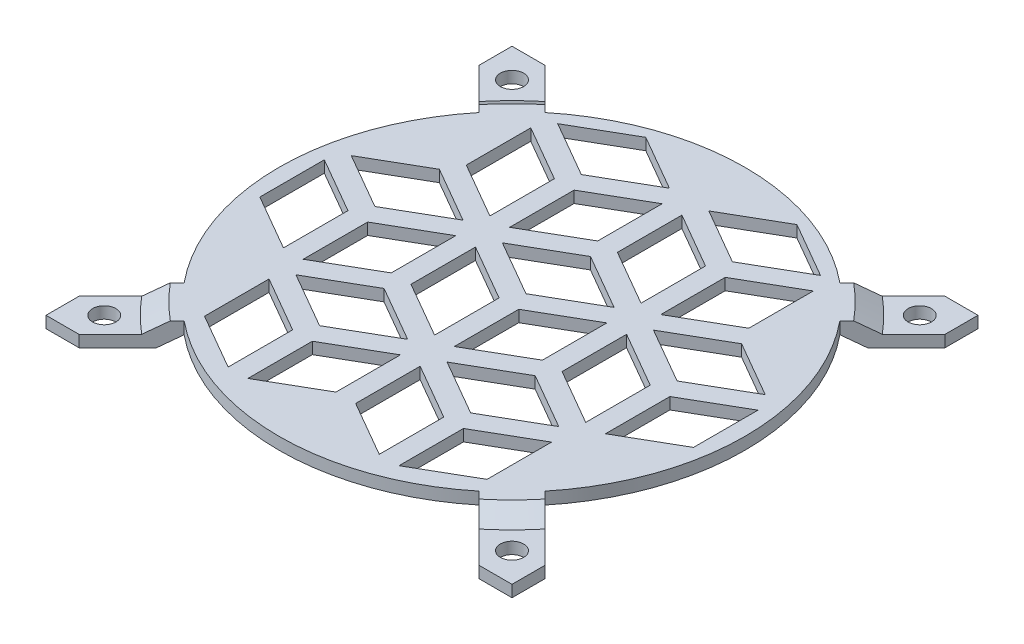
SolidWorks part; units mm, degrees
material "1.6523 (20NiCrMoS2-2)"
ref_plane "Спереди" through (0, 0, 0) normal (0, 0, 1) x (1, 0, 0)
ref_plane "Сверху" through (0, 0, 0) normal (0, 1, 0) x (1, 0, 0)
ref_plane "Справа" through (0, 0, 0) normal (1, 0, 0) x (0, 0, -1)
sketch "Эскиз1" plane through (0, 0, 0) normal (0, 1, 0) x (1, 0, 0)
  line L0 (-51.5147, -60) -> (-37.9711, -46.4564)
  line L1 (-60, 60) -> (-51.5147, 60)
  line L2 (-60, 60) -> (-60, 51.5147)
  line L3 (-60, -60) -> (-51.5147, -60)
  line L4 (60, 60) -> (60, 51.5147)
  line L5 (-60, 60) -> (60, -60) construction
  line L7 (-52.5, 52.5) -> (52.5, 52.5) construction
  line L8 (-52.5, 52.5) -> (-52.5, -52.5) construction
  line L9 (-52.5, -52.5) -> (52.5, -52.5) construction
  line L10 (52.5, 52.5) -> (52.5, -52.5) construction
  line L11 (-52.5, 52.5) -> (52.5, -52.5) construction
  line L13 (-60, -51.5147) -> (-46.4564, -37.9711)
  line L14 (-60, 51.5147) -> (-46.4564, 37.9711)
  line L15 (-51.5147, 60) -> (-37.9711, 46.4564)
  line L18 (51.5147, 60) -> (60, 60)
  line L20 (-60, -51.5147) -> (-60, -60)
  line L22 (-64.2426, 55.7574) -> (55.7574, -64.2426) construction
  line L23 (2.7392, 6.9819) -> (6.4592, 10.7018)
  line L25 (46.4564, -37.9711) -> (60, -51.5147)
  line L26 (-6.4592, 10.7018) -> (-2.7392, 6.9819)
  line L58 (-55.7574, 64.2426) -> (64.2426, -55.7574) construction
  line L59 (37.9711, -46.4564) -> (51.5147, -60)
  line L61 (46.4564, 37.9711) -> (60, 51.5147)
  line L65 (37.9711, 46.4564) -> (51.5147, 60)
  line L66 (60, -51.5147) -> (60, -60)
  line L67 (51.5147, -60) -> (60, -60)
  circle A10 centre (-52.5, -52.5) radius 3
  circle A11 centre (-52.5, 52.5) radius 3
  circle A12 centre (52.5, 52.5) radius 3
  circle A13 centre (52.5, -52.5) radius 3
  arc A14 (2.7392, 6.9819) -> (-2.7392, 6.9819) centre (0, 0) ccw
  arc A15 (6.4592, 10.7018) -> (-6.4592, 10.7018) centre (0, 0) ccw
  arc A44 (-37.9711, -46.4564) -> (37.9711, -46.4564) centre (0, 0) ccw
  arc A45 (46.4564, -37.9711) -> (46.4564, 37.9711) centre (0, 0) ccw
  arc A46 (37.9711, 46.4564) -> (-37.9711, 46.4564) centre (0, 0) ccw
  arc A47 (-46.4564, 37.9711) -> (-46.4564, -37.9711) centre (0, 0) ccw
  point P0 (0, 0)
  point P25 (-62.1213, 57.8787)
  point P26 (57.8787, -62.1213)
  point P27 (-57.8787, 62.1213)
  point P28 (62.1213, -57.8787)
  point P29 (-57.8787, -62.1213)
  point P30 (62.1213, 57.8787)
  point P31 (-62.1213, -57.8787)
  point P32 (57.8787, 62.1213)
  point P104 (-55.7574, -64.2426)
  point P105 (64.2426, 55.7574)
  point P106 (-64.2426, -55.7574)
  point P107 (55.7574, 64.2426)
  dimension "D15" = 6
  dimension "D16" = 6
  dimension "D17" = 6
  dimension "D18" = 6
  dimension "D1" = 120
  dimension "D2" = 120
  dimension "D13" = 105
  dimension "D14" = 105
  dimension "D21" = 6
  dimension "D22" = 6
extrude "Бобышка-Вытянуть1" add sketch "Эскиз1" along normal blind 6
sketch "Эскиз2" plane through (0, 0, 0) normal (0, -1, 0) x (1, 0, 0)
  circle A0 centre (0, 0) radius 65
  dimension "D1" = 130
extrude "Вырез-Вытянуть1" cut sketch "Эскиз2" against normal blind 3 draft 60
sketch "Эскиз3" plane through (0, 6, 0) normal (0, 1, 0) x (1, 0, 0)
  circle A0 centre (0, 0) radius 62.5
  dimension "D1" = 125
extrude "Вырез-Вытянуть2" cut sketch "Эскиз3" against normal blind 3 draft 60 flip side to cut
sketch "Sketch1" plane through (0, 6, 0) normal (0, 1, 0) x (1, 0, 0)
  line B0 (19.4556, 53.9141) -> (5.0736, 45.6106)
  line B1 (2.5356, 41.2147) -> (2.5356, 24.6078)
  line B2 (2.5356, 24.6078) -> (16.9176, 16.3043)
  line B3 (21.9936, 16.3043) -> (36.3756, 24.6078)
  line B4 (36.3756, 24.6078) -> (36.3756, 41.2147)
  line B5 (33.8376, 45.6106) -> (19.4556, 53.9141)
  line B6 (21.9936, 32.9112) -> (36.3756, 41.2147)
  line B7 (19.4556, 37.3072) -> (33.8376, 45.6106)
  line B8 (19.4556, 37.3072) -> (5.0736, 45.6106)
  line B9 (16.9176, 32.9112) -> (2.5356, 41.2147)
  line B10 (21.9936, 16.3043) -> (21.9936, 32.9112)
  line B11 (16.9176, 16.3043) -> (16.9176, 32.9112)
  line B12 (-19.4604, 53.9141) -> (-33.8424, 45.6106)
  line B13 (-36.3804, 41.2147) -> (-36.3804, 24.6078)
  line B14 (-36.3804, 24.6078) -> (-21.9984, 16.3043)
  line B15 (-16.9224, 16.3043) -> (-2.5404, 24.6078)
  line B16 (-2.5404, 24.6078) -> (-2.5404, 41.2147)
  line B17 (-5.0784, 45.6106) -> (-19.4604, 53.9141)
  line B18 (-16.9224, 32.9112) -> (-2.5404, 41.2147)
  line B19 (-19.4604, 37.3072) -> (-5.0784, 45.6106)
  line B20 (-19.4604, 37.3072) -> (-33.8424, 45.6106)
  line B21 (-21.9984, 32.9112) -> (-36.3804, 41.2147)
  line B22 (-16.9224, 16.3043) -> (-16.9224, 32.9112)
  line B23 (-21.9984, 16.3043) -> (-21.9984, 32.9112)
  line B24 (38.9136, 20.2118) -> (24.5316, 11.9084)
  line B25 (21.9936, 7.5124) -> (21.9936, -9.0945)
  line B26 (21.9936, -9.0945) -> (36.3756, -17.3979)
  line B27 (41.4516, -17.3979) -> (55.8336, -9.0945)
  line B28 (55.8336, -9.0945) -> (55.8336, 7.5124)
  line B29 (53.2956, 11.9084) -> (38.9136, 20.2118)
  line B30 (41.4516, -0.791) -> (55.8336, 7.5124)
  line B31 (38.9136, 3.6049) -> (53.2956, 11.9084)
  line B32 (38.9136, 3.6049) -> (24.5316, 11.9084)
  line B33 (36.3756, -0.791) -> (21.9936, 7.5124)
  line B34 (41.4516, -17.3979) -> (41.4516, -0.791)
  line B35 (36.3756, -17.3979) -> (36.3756, -0.791)
  line B36 (-2.5404, -42.7967) -> (-16.9224, -51.1002)
  line B37 (19.4556, -13.4904) -> (5.0736, -21.7939)
  line B38 (2.5356, -26.1898) -> (2.5356, -42.7967)
  line B39 (2.5356, -42.7967) -> (16.9176, -51.1002)
  line B40 (21.9936, -51.1002) -> (36.3756, -42.7967)
  line B41 (36.3756, -42.7967) -> (36.3756, -26.1898)
  line B42 (33.8376, -21.7939) -> (19.4556, -13.4904)
  line B43 (21.9936, -34.4933) -> (36.3756, -26.1898)
  line B44 (19.4556, -30.0973) -> (33.8376, -21.7939)
  line B45 (19.4556, -30.0973) -> (5.0736, -21.7939)
  line B46 (16.9176, -34.4933) -> (2.5356, -26.1898)
  line B47 (21.9936, -51.1002) -> (21.9936, -34.4933)
  line B48 (16.9176, -51.1002) -> (16.9176, -34.4933)
  line B49 (-19.4604, -13.4904) -> (-33.8424, -21.7939)
  line B50 (-36.3804, -26.1898) -> (-36.3804, -42.7967)
  line B51 (-36.3804, -42.7967) -> (-21.9984, -51.1002)
  line B52 (-2.5404, -42.7967) -> (-2.5404, -26.1898)
  line B53 (-5.0784, -21.7939) -> (-19.4604, -13.4904)
  line B54 (-16.9224, -34.4933) -> (-2.5404, -26.1898)
  line B55 (-19.4604, -30.0973) -> (-5.0784, -21.7939)
  line B56 (-19.4604, -30.0973) -> (-33.8424, -21.7939)
  line B57 (-21.9984, -34.4933) -> (-36.3804, -26.1898)
  line B58 (-16.9224, -51.1002) -> (-16.9224, -34.4933)
  line B59 (-21.9984, -51.1002) -> (-21.9984, -34.4933)
  line B60 (-21.9984, -9.0945) -> (-36.3804, -17.3979)
  line B61 (-0.0024, 20.2118) -> (-14.3844, 11.9084)
  line B62 (-16.9224, 7.5124) -> (-16.9224, -9.0945)
  line B63 (-16.9224, -9.0945) -> (-2.5404, -17.3979)
  line B64 (2.5356, -17.3979) -> (16.9176, -9.0945)
  line B65 (16.9176, -9.0945) -> (16.9176, 7.5124)
  line B66 (14.3796, 11.9084) -> (-0.0024, 20.2118)
  line B67 (2.5356, -0.791) -> (16.9176, 7.5124)
  line B68 (-0.0024, 3.6049) -> (14.3796, 11.9084)
  line B69 (-0.0024, 3.6049) -> (-14.3844, 11.9084)
  line B70 (-2.5404, -0.791) -> (-16.9224, 7.5124)
  line B71 (2.5356, -17.3979) -> (2.5356, -0.791)
  line B72 (-2.5404, -17.3979) -> (-2.5404, -0.791)
  line B73 (-38.9184, 20.2118) -> (-53.3004, 11.9084)
  line B74 (-55.8384, 7.5124) -> (-55.8384, -9.0945)
  line B75 (-55.8384, -9.0945) -> (-41.4564, -17.3979)
  line B76 (-21.9984, -9.0945) -> (-21.9984, 7.5124)
  line B77 (-24.5364, 11.9084) -> (-38.9184, 20.2118)
  line B78 (-36.3804, -0.791) -> (-21.9984, 7.5124)
  line B79 (-38.9184, 3.6049) -> (-24.5364, 11.9084)
  line B80 (-38.9184, 3.6049) -> (-53.3004, 11.9084)
  line B81 (-41.4564, -0.791) -> (-55.8384, 7.5124)
  line B82 (-36.3804, -17.3979) -> (-36.3804, -0.791)
  line B83 (-41.4564, -17.3979) -> (-41.4564, -0.791)
sketch_block_instance "Block1-1"
sketch_block "Block1"
extrude "Cut-Extrude1" cut sketch "Sketch1" against normal through all
